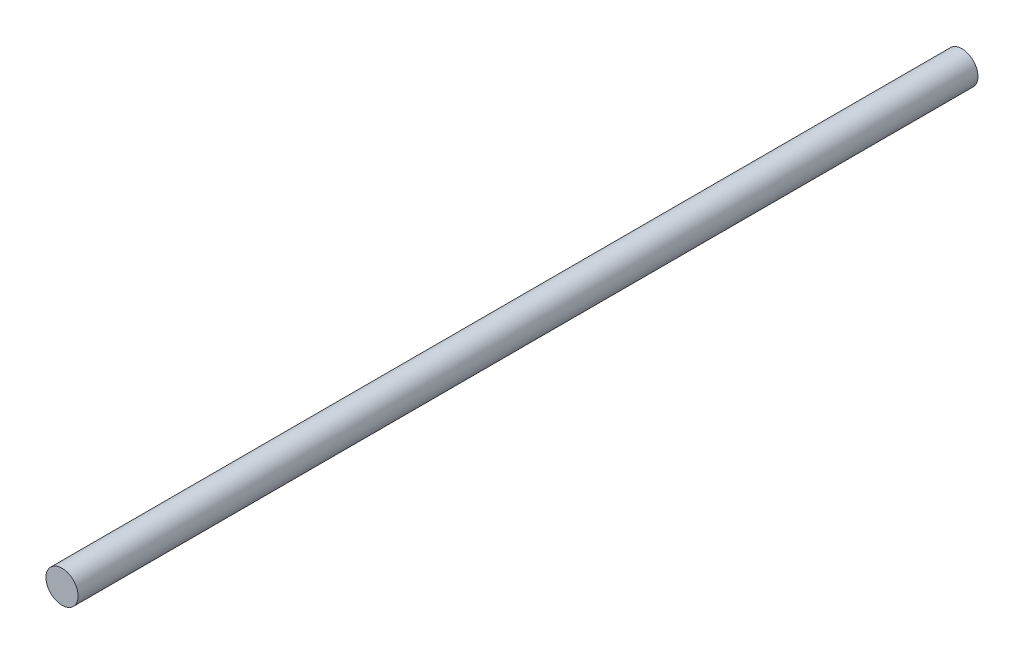
SolidWorks part; units mm, degrees
ref_plane "前视基准面" through (0, 0, 0) normal (0, 0, 1) x (1, 0, 0)
ref_plane "上视基准面" through (0, 0, 0) normal (0, 1, 0) x (1, 0, 0)
ref_plane "右视基准面" through (0, 0, 0) normal (1, 0, 0) x (0, 0, -1)
other "Configuration Table"
sketch "草图1" plane through (0, 0, 0) normal (0, 0, 1) x (1, 0, 0)
  circle A0 centre (0, 0) radius 5
extrude "凸台-拉伸1" add sketch "草图1" along normal blind 280
